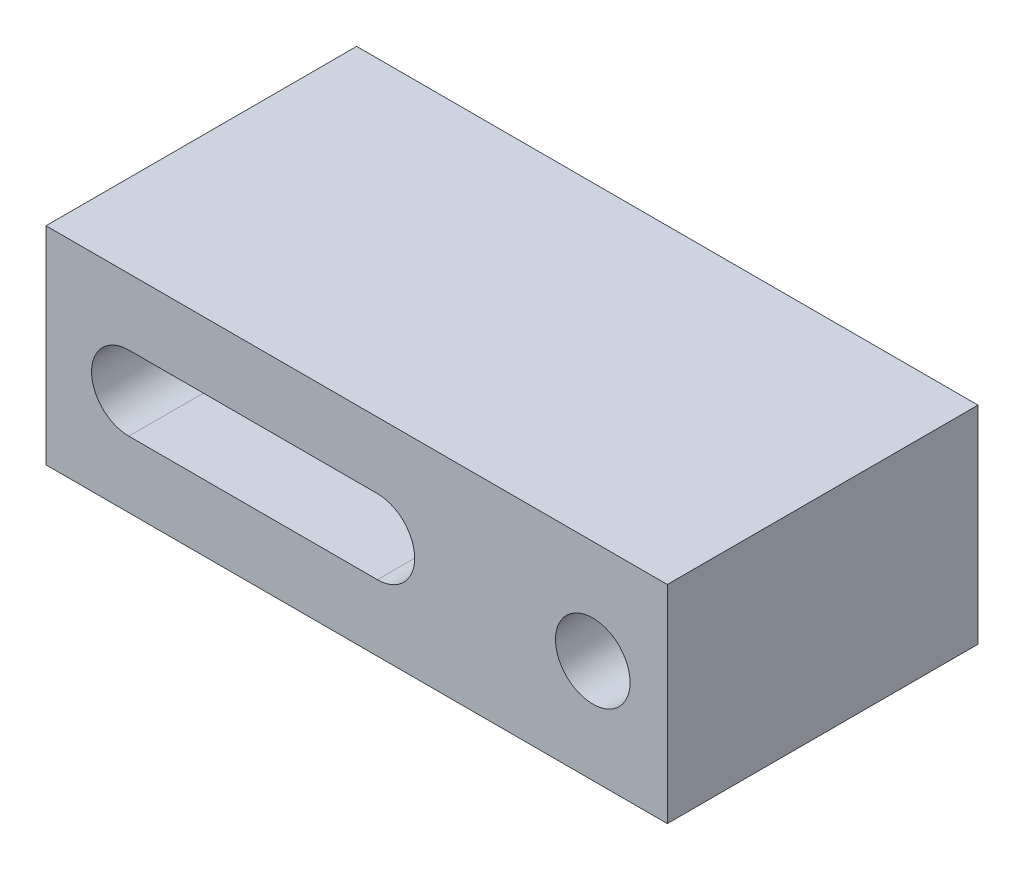
SolidWorks part; units mm, degrees
ref_plane "Front Plane" through (0, 0, 0) normal (0, 0, 1) x (1, 0, 0)
ref_plane "Top Plane" through (0, 0, 0) normal (0, 1, 0) x (1, 0, 0)
ref_plane "Right Plane" through (0, 0, 0) normal (1, 0, 0) x (0, 0, -1)
sketch "Sketch1" plane through (0, 0, 0) normal (0, 1, 0) x (1, 0, 0)
  line L1 (-750, 375) -> (750, 375)
  line L2 (-750, 375) -> (-750, -375)
  line L3 (-750, -375) -> (750, -375)
  line L4 (750, 375) -> (750, -375)
  line L5 (-750, 375) -> (750, -375) construction
  line L6 (-750, -375) -> (750, 375) construction
  point P0 (0, 0)
  dimension "D1" = 1500
  dimension "D2" = 750
extrude "Boss-Extrude1" add sketch "Sketch1" along normal blind 500
sketch "Sketch2" plane through (0, 0, 375) normal (0, 0, 1) x (1, 0, 0)
  line L0 (-750, 250) -> (750, 250) construction
  line L1 (-750, 500) -> (-750, 0) construction
  line L2 (750, 500) -> (750, 0) construction
  line L3 (-550, 250) -> (50, 250) construction
  line L4 (-550, 340) -> (50, 340)
  line L5 (-550, 160) -> (50, 160)
  arc A0 (-550, 340) -> (-550, 160) centre (-550, 250) ccw
  arc A1 (50, 160) -> (50, 340) centre (50, 250) ccw
  circle A2 centre (570, 250) radius 90
  point P8 (-250, 250)
  dimension "D2" = 600
  dimension "D3" = 200
  dimension "D4" = 180
  dimension "D5" = 180
  dimension "D1" = 180
extrude "Cut-Extrude1" cut sketch "Sketch2" against normal through all
